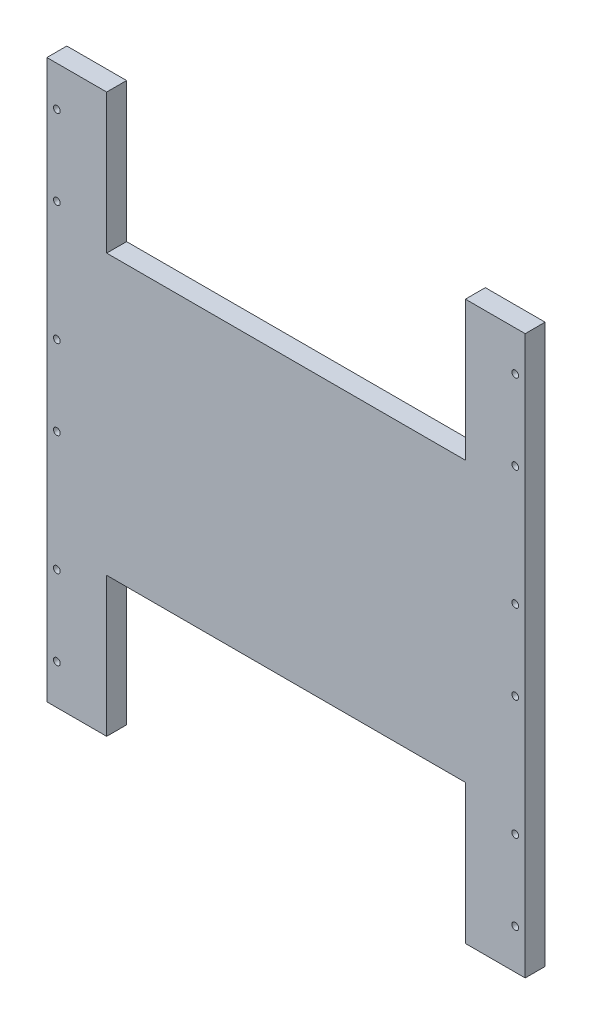
SolidWorks part; units mm, degrees
ref_plane "Front Plane" through (0, 0, 0) normal (0, 0, 1) x (1, 0, 0)
ref_plane "Top Plane" through (0, 0, 0) normal (0, 1, 0) x (1, 0, 0)
ref_plane "Right Plane" through (0, 0, 0) normal (1, 0, 0) x (0, 0, -1)
sketch "Sketch1" plane through (0, 0, 0) normal (0, 0, 1) x (1, 0, 0)
  line L1 (0, 0) -> (304.8, 0)
  line L2 (0, 0) -> (0, 355.6)
  line L3 (0, 355.6) -> (304.8, 355.6)
  line L4 (304.8, 0) -> (304.8, 355.6)
  dimension "D1" = 304.8
  dimension "D2" = 355.6
extrude "Boss-Extrude1" add sketch "Sketch1" along normal blind 12.7
sketch "Sketch2" plane through (0, 0, 12.7) normal (0, 0, 1) x (1, 0, 0)
  line L0 (152.4, 355.6) -> (152.4, 0) construction
  line L1 (304.8, 355.6) -> (0, 355.6) construction
  line L2 (0, 0) -> (304.8, 0) construction
  line L3 (0, 44.45) -> (38.1, 44.45) construction
  line L4 (38.1, 0) -> (266.7, 0)
  line L5 (38.1, 0) -> (38.1, 88.9)
  line L6 (38.1, 88.9) -> (266.7, 88.9)
  line L7 (266.7, 0) -> (266.7, 88.9)
  line L8 (0, 355.6) -> (0, 0) construction
  line L9 (266.7, 44.45) -> (304.8, 44.45) construction
  line L10 (304.8, 0) -> (304.8, 355.6) construction
  line L11 (0, 177.8) -> (304.8, 177.8) construction
  line L12 (38.1, 355.6) -> (266.7, 355.6)
  line L13 (266.7, 355.6) -> (266.7, 266.7)
  line L14 (38.1, 355.6) -> (38.1, 266.7)
  line L15 (38.1, 266.7) -> (266.7, 266.7)
  dimension "D1" = 88.9
  dimension "D2" = 228.6
extrude "Cut-Extrude1" cut sketch "Sketch2" against normal through all
sketch "Sketch3" plane through (0, 0, 12.7) normal (0, 0, 1) x (1, 0, 0)
  line L0 (38.1, 355.6) -> (0, 355.6) construction
  line L1 (0, 355.6) -> (0, 0) construction
  line L2 (0, 177.8) -> (304.8, 177.8) construction
  line L3 (304.8, 0) -> (304.8, 355.6) construction
  line L4 (152.4, 266.7) -> (152.4, 88.9) construction
  line L5 (38.1, 266.7) -> (266.7, 266.7) construction
  line L6 (266.7, 88.9) -> (38.1, 88.9) construction
  line L7 (0, 241.3) -> (304.8, 241.3) construction
  circle A0 centre (6.35, 330.2) radius 2.159
  circle A1 centre (6.35, 279.4) radius 2.159
  circle A2 centre (6.35, 76.2) radius 2.159
  circle A3 centre (6.35, 25.4) radius 2.159
  circle A4 centre (298.45, 25.4) radius 2.159
  circle A5 centre (298.45, 76.2) radius 2.159
  circle A6 centre (298.45, 279.4) radius 2.159
  circle A7 centre (298.45, 330.2) radius 2.159
  circle A8 centre (6.35, 203.2) radius 2.159
  circle A9 centre (6.35, 152.4) radius 2.159
  circle A10 centre (298.45, 152.4) radius 2.159
  circle A11 centre (298.45, 203.2) radius 2.159
  dimension "D1" = 4.318
  dimension "D2" = 4.318
  dimension "D3" = 50.8
  dimension "D4" = 25.4
  dimension "D5" = 6.35
  dimension "D6" = 63.5
extrude "Cut-Extrude2" cut sketch "Sketch3" against normal through all
